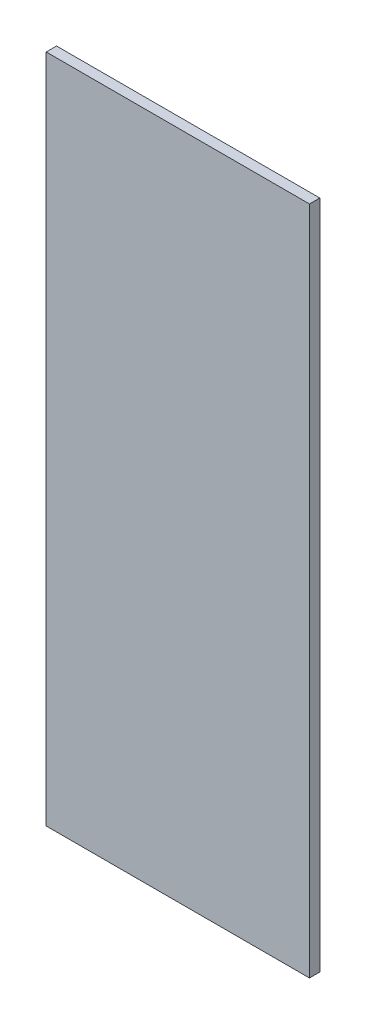
SolidWorks part; units mm, degrees
material "Polyurethane Foam Rigid"
ref_plane "Front Plane" through (0, 0, 0) normal (0, 0, 1) x (1, 0, 0)
ref_plane "Top Plane" through (0, 0, 0) normal (0, 1, 0) x (1, 0, 0)
ref_plane "Right Plane" through (0, 0, 0) normal (1, 0, 0) x (0, 0, -1)
sketch "Sketch1" plane through (0, 0, 0) normal (0, 0, 1) x (1, 0, 0)
  line L1 (-324, -825) -> (324, -825)
  line L2 (-324, -825) -> (-324, 825)
  line L3 (-324, 825) -> (324, 825)
  line L4 (324, -825) -> (324, 825)
  line L5 (-324, -825) -> (324, 825) construction
  line L6 (-324, 825) -> (324, -825) construction
  point P0 (0, 0)
  dimension "D1" = 648
  dimension "D2" = 1650
extrude "Boss-Extrude1" add sketch "Sketch1" along normal blind 25.4
